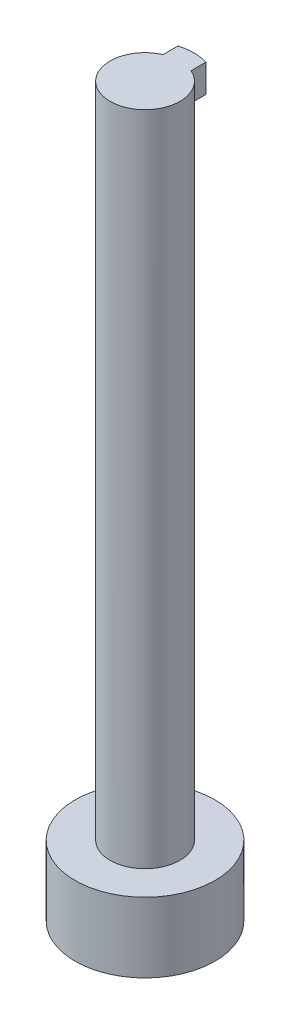
SolidWorks part; units mm, degrees
ref_plane "Front Plane" through (0, 0, 0) normal (0, 0, 1) x (1, 0, 0)
ref_plane "Top Plane" through (0, 0, 0) normal (0, 1, 0) x (1, 0, 0)
ref_plane "Right Plane" through (0, 0, 0) normal (1, 0, 0) x (0, 0, -1)
sketch "Sketch1" plane through (0, 0, 0) normal (0, 1, 0) x (1, 0, 0)
  circle A0 centre (0, 0) radius 3.175
  dimension "D1" = 6.35
extrude "Boss-Extrude1" add sketch "Sketch1" along normal blind 66.04 contours A0
sketch "Sketch2" plane through (0, 66.04, 0) normal (0, 1, 0) x (1, 0, 0)
  line L0 (0, 0) -> (0, 3.175) construction
  line L1 (0, 3.175) -> (0, 4.445) construction
  line L3 (1.27, 4.2597) -> (1.27, 2.9099)
  line L4 (-1.27, 4.2597) -> (-1.27, 2.9099)
  circle A0 centre (0, 0) radius 3.175 construction
  arc A1 (1.27, 4.2597) -> (-1.27, 4.2597) centre (0, 0) ccw
  arc A2 (1.27, 2.9099) -> (-1.27, 2.9099) centre (0, 0) ccw
  dimension "D2" = 2.54
  dimension "D1" = 1.27
extrude "Boss-Extrude2" add sketch "Sketch2" against normal blind 2.54
sketch "Sketch3" plane through (0, 0, 0) normal (0, -1, 0) x (1, 0, 0)
  circle A0 centre (0, 0) radius 6.35
  circle A1 centre (0, 0) radius 3.175
  dimension "D1" = 12.7
extrude "Boss-Extrude3" add sketch "Sketch3" against normal blind 6.35
